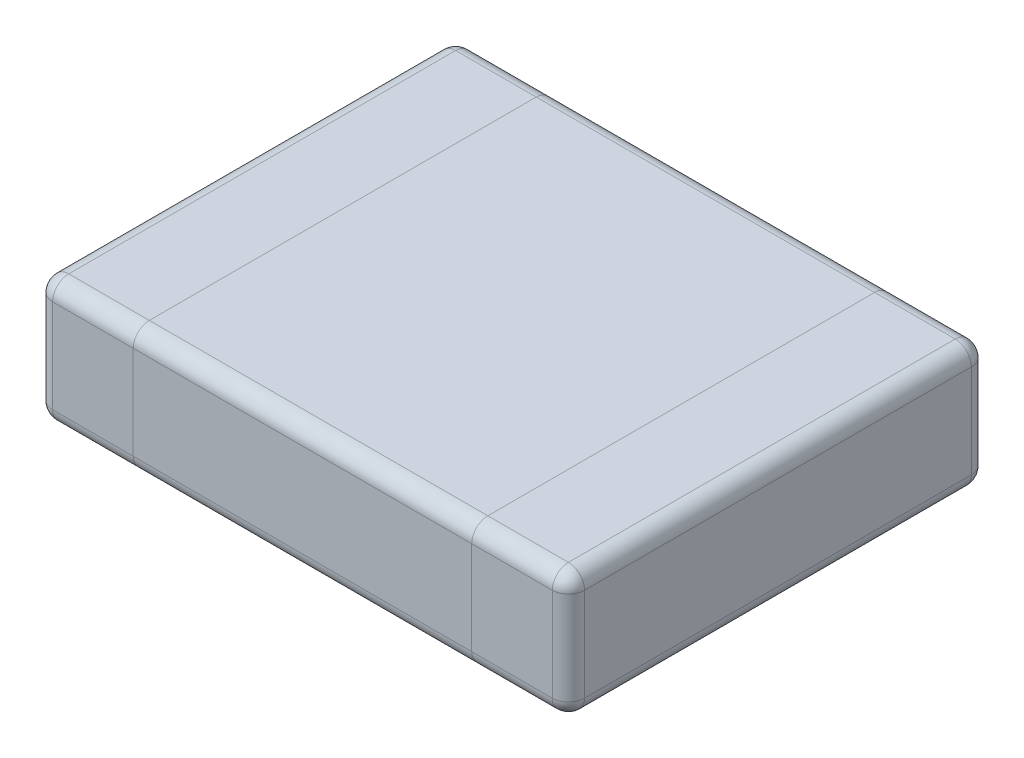
SolidWorks part; units mm, degrees
ref_plane "Alzado" through (0, 0, 0) normal (0, 0, 1) x (1, 0, 0)
ref_plane "Planta" through (0, 0, 0) normal (0, 1, 0) x (1, 0, 0)
ref_plane "Vista lateral" through (0, 0, 0) normal (1, 0, 0) x (0, 0, -1)
sketch "Croquis1" plane through (0, 0, 0) normal (0, 1, 0) x (1, 0, 0)
  line L1 (-1.05, -1.3) -> (1.05, -1.3)
  line L2 (-1.05, -1.3) -> (-1.05, 1.3)
  line L3 (-1.05, 1.3) -> (1.05, 1.3)
  line L4 (1.05, -1.3) -> (1.05, 1.3)
  line L5 (-1.05, -1.3) -> (1.05, 1.3) construction
  line L6 (-1.05, 1.3) -> (1.05, -1.3) construction
  point P0 (0, 0)
  dimension "D1" = 2.1
  dimension "D2" = 2.6
extrude "Saliente-Extruir1" add sketch "Croquis1" along normal blind 0.78
sketch "Croquis3" plane through (0, 0, 0) normal (0, 1, 0) x (1, 0, 0)
  line L0 (1.05, 1.3) -> (1.65, 1.3)
  line L1 (1.65, 1.3) -> (1.65, -1.3)
  line L2 (1.65, -1.3) -> (1.05, -1.3)
  line L3 (1.05, -1.3) -> (1.05, 1.3) construction
  line L4 (1.05, -1.3) -> (1.05, 1.3)
  line L5 (0, 1.3421) -> (0, -1.4057) construction
  line L6 (-1.05, -1.3) -> (-1.05, 1.3)
  line L7 (-1.65, -1.3) -> (-1.05, -1.3)
  line L8 (-1.65, 1.3) -> (-1.65, -1.3)
  line L9 (-1.05, 1.3) -> (-1.65, 1.3)
  dimension "D1" = 0.6
extrude "Saliente-Extruir3" add sketch "Croquis3" along normal blind 0.78 separate body
fillet "Redondeo2" radius 0.1 4 edges at (0, 0, 1.3) (0, 0.78, 1.3) (0, 0, -1.3) (0, 0.78, -1.3)
fillet "Redondeo4" radius 0.1 8 edges at (1.65, 0.39, 1.3) (1.65, 0.78, 0) (1.65, 0.39, -1.3) (1.65, 0, 0) (1.35, 0, 1.3) (1.35, 0.78, 1.3) (1.35, 0.78, -1.3) (1.35, 0, -1.3)
fillet "Redondeo5" radius 0.1 8 edges at (-1.65, 0.39, -1.3) (-1.65, 0.78, 0) (-1.65, 0.39, 1.3) (-1.65, 0, 0) (-1.35, 0, -1.3) (-1.35, 0.78, -1.3) (-1.35, 0, 1.3) (-1.35, 0.78, 1.3)
